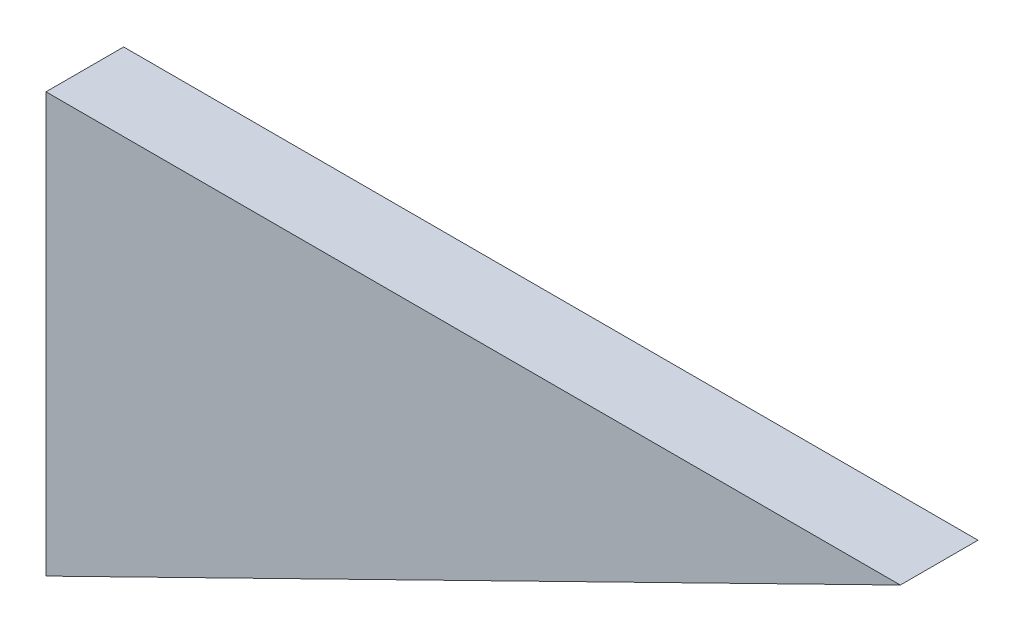
SolidWorks part; units mm, degrees
ref_plane "前视基准面" through (0, 0, 0) normal (0, 0, 1) x (1, 0, 0)
ref_plane "上视基准面" through (0, 0, 0) normal (0, 1, 0) x (1, 0, 0)
ref_plane "右视基准面" through (0, 0, 0) normal (1, 0, 0) x (0, 0, -1)
other "Configuration Table"
sketch "草图1" plane through (0, 0, 0) normal (0, 0, 1) x (1, 0, 0)
  line L0 (0, 0) -> (55, 0)
  line L1 (55, 0) -> (0, -27)
  line L2 (0, -27) -> (0, 0)
  dimension "x1" = 55
  dimension "y2" = 27
extrude "Support_gusset" add sketch "草图1" along normal blind 5
